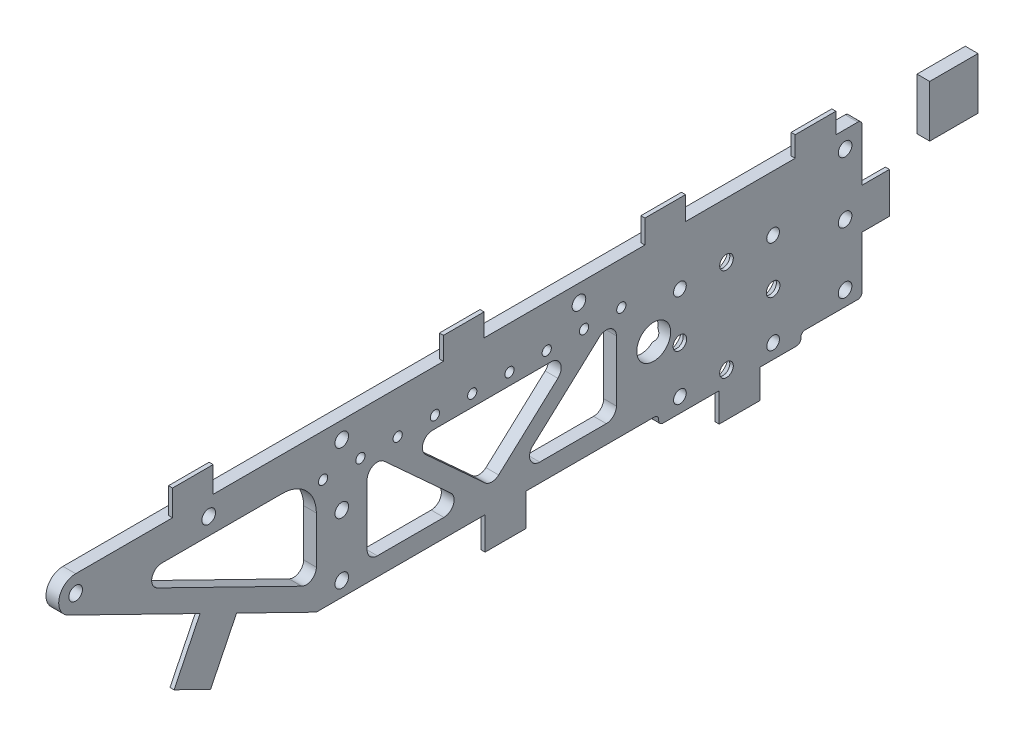
SolidWorks part; units mm, degrees
material "6061-T6 (SS)"
ref_plane "Front Plane" through (0, 0, 0) normal (0, 0, 1) x (1, 0, 0)
ref_plane "Top Plane" through (0, 0, 0) normal (0, 1, 0) x (1, 0, 0)
ref_plane "Right Plane" through (0, 0, 0) normal (1, 0, 0) x (0, 0, -1)
sketch "Sketch1" plane through (0, 0, 0) normal (1, 0, 0) x (0, 0, -1)
  line L0 (0, 0) -> (407.9875, 0) construction
  line L1 (407.9875, 76.2) -> (363.8474, 76.2) construction
  line L2 (407.9875, 76.2) -> (337.2485, 76.2) construction
  line L3 (0, 2.286) -> (405.7015, 2.286) construction
  line L7 (399.161, 66.167) -> (399.161, 8.5725)
  line L8 (373.761, 2.4765) -> (322.961, 2.4765) construction
  line L9 (373.761, 2.4765) -> (373.761, 53.2765) construction
  line L10 (373.761, 53.2765) -> (322.961, 53.2765) construction
  line L11 (322.961, 2.4765) -> (322.961, 53.2765) construction
  line L12 (407.9875, 0) -> (407.9875, 76.2) construction
  line L13 (405.7015, 2.286) -> (405.7015, 73.914) construction
  line L14 (405.7015, 73.914) -> (337.2485, 73.914) construction
  line L15 (405.7015, 73.914) -> (363.8474, 73.914) construction
  line L16 (373.9515, 2.286) -> (373.9515, 33.9264) construction
  line L17 (370.586, 50.1015) -> (326.136, 50.1015) construction
  line L18 (326.136, 5.6515) -> (326.136, 50.1015) construction
  line L19 (370.586, 5.6515) -> (326.136, 5.6515) construction
  line L20 (370.586, 5.6515) -> (370.586, 50.1015) construction
  line L21 (330.8985, 10.414) -> (330.8985, 45.339) construction
  line L22 (365.8235, 45.339) -> (330.8985, 45.339) construction
  line L23 (365.8235, 10.414) -> (365.8235, 45.339) construction
  line L24 (365.8235, 10.414) -> (330.8985, 10.414) construction
  line L25 (-107.0632, 2.286) -> (405.7015, 2.286) construction
  line L26 (-107.0632, 0) -> (407.9875, 0) construction
  line L27 (376.2375, 2.286) -> (376.2375, 33.9264) construction
  line L28 (373.9515, 33.9264) -> (376.2375, 33.9264) construction
  line L29 (337.2485, 76.2) -> (337.2485, 73.914) construction
  line L30 (0, 28.3777) -> (329.9656, 33.1402) construction
  line L31 (329.9656, 33.1402) -> (321.0756, 33.1402) construction
  line L32 (194.6275, 71.628) -> (194.6275, 2.286) construction
  line L33 (213.6775, 2.286) -> (213.6775, 71.628) construction
  line L34 (194.6275, 2.286) -> (213.6775, 2.286) construction
  line L35 (194.6275, 71.628) -> (213.6775, 71.628) construction
  line L36 (399.161, 71.628) -> (0, 71.628) construction
  line L37 (94.8817, 71.628) -> (113.9317, 71.628) construction
  line L38 (94.8817, 71.628) -> (94.8817, 2.286) construction
  line L39 (94.8817, 2.286) -> (113.9317, 2.286) construction
  line L40 (113.9317, 71.628) -> (113.9317, 2.286) construction
  line L41 (343.7851, 73.914) -> (343.7851, 71.628) construction
  line L42 (405.7015, 4.7625) -> (0, 4.7625) construction
  line L43 (204.1525, 59.817) -> (204.1525, 14.097) construction
  line L44 (204.1525, 36.957) -> (213.6775, 36.957) construction
  line L45 (104.4067, 59.817) -> (104.4067, 14.097) construction
  line L46 (399.161, 66.167) -> (104.4067, 66.167)
  line L47 (322.961, 8.5725) -> (322.961, 4.953)
  line L48 (322.961, 4.953) -> (376.2375, 4.953)
  line L50 (376.2375, 4.953) -> (376.2375, 8.5725)
  line L51 (376.2375, 8.5725) -> (399.161, 8.5725)
  line L52 (204.1525, 59.817) -> (104.4067, 59.817) construction
  line L53 (104.4067, 53.467) -> (194.6275, 53.467)
  line L54 (194.6275, 8.5725) -> (194.6275, 53.467)
  line L55 (194.6275, 8.5725) -> (322.961, 8.5725)
  line L56 (392.811, 59.817) -> (392.811, 14.097) construction
  line L57 (204.1525, 59.817) -> (392.811, 59.817) construction
  line L58 (392.811, 71.628) -> (392.811, 59.817) construction
  line L64 (405.7015, 73.914) -> (0, 73.914) construction
  circle A0 centre (330.8985, 45.339) radius 2.3813
  circle A1 centre (365.8235, 45.339) radius 2.3813
  circle A2 centre (330.8985, 10.414) radius 2.3813
  circle A3 centre (365.8235, 10.414) radius 2.3813
  circle A4 centre (321.0756, 33.1402) radius 6.35
  circle A5 centre (0, 28.3777) radius 22.2817 construction
  arc A6 (104.4067, 53.467) -> (104.4067, 66.167) centre (104.4067, 59.817) cw
  point P54 (204.1525, 2.286)
  point P66 (104.4067, 36.957)
  point P67 (104.4067, 2.286)
  dimension "D19" = 12.7
  dimension "D20" = 44.5634
  dimension "D3" = 50.8
  dimension "D2" = 0.1905
  dimension "D9" = 34.925
  dimension "D13" = 407.9875
  dimension "D14" = 0.1905
  dimension "D4" = 31.75
  dimension "D15" = 330
  dimension "D17" = 4.7625
  dimension "D18" = 8.89
  dimension "D21" = 3.81
  dimension "D16" = 19.05
  dimension "D25" = 45.72
  dimension "D22" = 213.36
  dimension "D7" = 104.4067
  dimension "D24" = 0.1905
  dimension "D11" = 6.35
  dimension "D23" = 12.8905
  dimension "D12" = 6.35
  dimension "D8" = 3.175
extrude "Boss-Extrude1" add sketch "Sketch1" along normal blind 4.7625
hole_wizard "CSK for #10 Flat Head Socket Cap Screw1" positions "Sketch2" profile "Sketch3" countersink size "#10" standard "ANSI Inch" end condition through all
sketch "Sketch2" plane through (0, 0, 0) normal (-1, 0, 0) x (0, 0, 1)
  line L0 (-365.8235, 45.339) -> (-330.8985, 10.414) construction
  line L9 (-365.8235, 27.8765) -> (-330.8985, 27.8765) construction
  line L11 (-348.361, 45.339) -> (-348.361, 10.414) construction
  point P58 (-348.361, 27.8765)
  point P59 (-348.361, 27.8765)
  point P62 (-348.361, 45.339)
  point P65 (-330.8985, 27.8765)
  point P68 (-365.8235, 27.8765)
  point P71 (-348.361, 10.414)
sketch "Sketch3" plane through (0, 10.414, -348.361) normal (0, 1, 0) x (0, 0, 1)
  line L0 (0, 0) -> (0, 4.7625)
  line L1 (0, 4.7625) -> (2.5527, 4.7625)
  line L2 (2.5527, 4.7625) -> (2.5527, 3.449)
  line L3 (2.5527, 3.449) -> (5.5509, 0)
  line L5 (5.5509, 0) -> (0, 0)
  line L6 (-2.5527, 3.449) -> (-5.5509, 0) construction
  line L11 (0, -6.35) -> (0, 107.95) construction
  dimension "Thru Hole Dia." = 5.1054
  dimension "Thru Hole Depth" = 4.7625
  dimension "Near C'Sink Dia." = 11.1018
  dimension "Near C'Sink Angle" = 82
sketch "Sketch13" plane through (0, 0, 0) normal (-1, 0, 0) x (0, 0, 1)
  line L0 (-194.6275, 8.5725) -> (-101.6143, 54.1139)
  line L1 (-194.6275, 17.0569) -> (-120.2639, 53.467)
  line L2 (-194.6275, 53.467) -> (-194.6275, 8.5725) construction
  line L3 (-104.4067, 53.467) -> (-194.6275, 53.467) construction
  line L4 (-194.6275, 17.0569) -> (-194.6275, 8.5725)
  line L5 (-120.2639, 53.467) -> (-101.6143, 54.1139)
  arc A0 (-104.4067, 53.467) -> (-104.4067, 66.167) centre (-104.4067, 59.817) ccw construction
  dimension "D1" = 7.62
extrude "Boss-Extrude3" add sketch "Sketch13" against normal up to vertex (4.7625 mm away) up to point (4.7625, 8.5725, -194.6275)
fillet "Fillet1" radius 1.5875 7 edges at (2.3813, 66.167, -399.161) (2.3813, 4.953, -376.2375) (2.3813, 4.953, -322.961) (2.3813, 8.5725, -376.2375) (2.3813, 8.5725, -399.161) (2.3813, 8.5725, -322.961) (2.3813, 8.5725, -194.6275)
fillet "Fillet2" radius 12.7 1 edges at (2.3813, 53.467, -194.6275)
hole_wizard "#10 Clearance Hole1" positions "Sketch8" profile "Sketch9" hole size "#10" standard "ANSI Inch" end condition through all
sketch "Sketch8" plane through (4.7625, 0, 0) normal (1, 0, 0) x (0, 0, -1)
  line L1 (204.1525, 59.817) -> (204.1525, 14.097) construction
  line L6 (204.1525, 59.817) -> (104.4067, 59.817) construction
  line L7 (392.811, 59.817) -> (392.811, 14.097) construction
  line L8 (204.1525, 59.817) -> (293.0525, 59.817) construction
  line L9 (204.1525, 59.817) -> (392.811, 59.817) construction
  line L10 (293.0525, 59.817) -> (392.811, 59.817) construction
  point P10 (204.1525, 59.817)
  point P13 (204.1525, 36.957)
  point P17 (204.1525, 14.097)
  point P30 (154.2796, 59.817)
  point P34 (392.811, 59.817)
  point P37 (392.811, 36.957)
  point P41 (392.811, 14.097)
  point P56 (293.0525, 59.817)
  point P68 (104.4067, 59.817)
  dimension "D1" = 88.9
sketch "Sketch9" plane through (4.7625, 59.817, -204.1525) normal (0, 1, 0) x (0, 0, -1)
  line L0 (0, 0) -> (0, 5.0174)
  line L1 (0, 5.0174) -> (2.5527, 5.0174)
  line L2 (2.5527, 5.0174) -> (2.5527, 0)
  line L5 (2.5527, 0) -> (0, 0)
  line L11 (0, -6.35) -> (0, 107.95) construction
  dimension "Thru Hole Dia." = 5.1054
  dimension "Thru Hole Depth" = 5.0174
sketch "Sketch14" plane through (0, 0, 0) normal (-1, 0, 0) x (0, 0, 1)
  line L0 (-194.6275, 36.957) -> (-213.6775, 36.957) construction
  line L1 (-307.1056, 15.4305) -> (-213.6775, 15.4305)
  line L2 (-307.1056, 15.4305) -> (-307.1056, 45.847)
  line L3 (-307.1056, 45.847) -> (-213.6775, 45.847)
  line L4 (-213.6775, 15.4305) -> (-213.6775, 45.847)
  line L5 (-194.6275, 40.767) -> (-194.6275, 17.0569) construction
  line L6 (-194.9953, 8.5725) -> (-321.3735, 8.5725) construction
  line L7 (-252.2487, 15.4305) -> (-218.9662, 45.847)
  line L8 (-261.6616, 15.4305) -> (-228.3791, 45.847)
  line L9 (-397.5735, 66.167) -> (-104.4067, 66.167) construction
  line L10 (-259.1216, 15.4305) -> (-292.4041, 45.847)
  line L11 (-268.5344, 15.4305) -> (-300.7254, 44.8494)
  line L12 (-245.0203, 30.6387) -> (-240.7365, 25.9513) construction
  line L13 (-275.7628, 30.6387) -> (-280.0466, 25.9513) construction
  circle A0 centre (-204.1525, 36.957) radius 2.5527 construction
  arc A1 (-213.6775, 42.037) -> (-220.0578, 44.8494) centre (-217.4875, 42.037) ccw
  arc A2 (-300.7254, 44.8494) -> (-307.1056, 42.037) centre (-303.2956, 42.037) ccw
  arc A3 (-325.3796, 28.4713) -> (-327.3467, 32.1424) centre (-321.0756, 33.1402) ccw construction
  point P8 (-204.1525, 36.957)
  dimension "D2" = 3.81
  dimension "D6" = 2.54
  dimension "D1" = 6.858
  dimension "D3" = 6.35
  dimension "D4" = 20.32
  dimension "D5" = 7.62
extrude "Cut-Extrude1" cut sketch "Sketch14" against normal through all contours L10 L8 L3 | L4 A1 L7 L1 | L11 A2 L2 L1
fillet "Fillet3" radius 3.81 9 edges at (2.3813, 17.0569, -194.6275) (2.3813, 53.467, -120.2639) (2.3813, 15.4305, -252.2487) (2.3813, 15.4305, -213.6775) (2.3813, 15.4305, -307.1056) (2.3813, 15.4305, -268.5344) (2.3813, 45.847, -228.3791) (2.3813, 16.5911, -260.3916) (2.3813, 45.847, -292.4041)
sketch "Sketch10" [suppressed] plane through (4.7625, 0, 0) normal (1, 0, 0) x (0, 0, -1)
  line L0 (196.215, 8.5725) -> (170.815, 8.5725)
  line L1 (169.2275, 10.16) -> (169.2275, 40.767)
  line L2 (136.7096, 53.467) -> (181.9275, 53.467) construction
  line L3 (156.5275, 53.467) -> (196.215, 53.467)
  line L4 (196.215, 53.467) -> (196.215, 8.5725)
  line L5 (194.6275, 40.767) -> (194.6275, 23.1645) construction
  arc A0 (170.815, 8.5725) -> (169.2275, 10.16) centre (170.815, 10.16) cw
  arc A1 (169.2275, 40.767) -> (156.5275, 53.467) centre (156.5275, 40.767) ccw
  arc A2 (194.6275, 40.767) -> (181.9275, 53.467) centre (181.9275, 40.767) ccw construction
  arc A3 (194.6275, 10.16) -> (196.215, 8.5725) centre (196.215, 10.16) ccw construction
  dimension "D1" = 25.4
extrude "Boss-Extrude2" [suppressed] add sketch "Sketch10" against normal up to vertex
hole_wizard "#8-32 Tapped Hole1" positions "Sketch11" profile "Sketch12" tap size "#8-32" standard "ANSI Inch"
sketch "Sketch11" plane through (4.7625, 0, 0) normal (1, 0, 0) x (0, 0, -1)
  line L5 (280.9875, 50.292) -> (308.9275, 50.292) construction
  circle A0 centre (204.1525, 59.817) radius 2.5527 construction
  point P0 (197.1675, 50.292)
  point P12 (211.1375, 50.292)
  point P13 (225.1075, 50.292)
  point P14 (239.0775, 50.292)
  point P15 (253.0475, 50.292)
  point P16 (267.0175, 50.292)
  point P17 (280.9875, 50.292)
  point P18 (294.9575, 50.292)
  point P41 (308.9275, 50.292)
  point P43 (204.1525, 35.052) [skipped]
  point P44 (301.9425, 35.052) [skipped]
  point P45 (287.9725, 35.052) [skipped]
  point P46 (274.0025, 35.052) [skipped]
  point P47 (260.0325, 35.052) [skipped]
  point P48 (246.0625, 35.052) [skipped]
  point P49 (232.0925, 35.052) [skipped]
  point P50 (218.1225, 35.052) [skipped]
  dimension "D1" = 9.525
  dimension "D2" = 6.985
  dimension "D5" = 13.97
  dimension "D3" = 8
  dimension "D4" = 2
sketch "Sketch12" plane through (4.7625, 50.292, -197.1675) normal (0, 1, 0) x (0, 0, -1)
  line L0 (0, 0) -> (0, 5.0174)
  line L1 (0, 5.0174) -> (1.7272, 5.0174)
  line L2 (1.7272, 5.0174) -> (1.7272, 0)
  line L5 (1.7272, 0) -> (0, 0)
  line L11 (0, -6.35) -> (0, 107.95) construction
  dimension "Thru Tap Drill Dia." = 3.4544
  dimension "Thru Tap Drill Depth" = 5.0174
cosmetic thread "Hole Thread1" parameters "D2"=4.1656
cosmetic thread "Hole Thread13" parameters "D2"=4.1656
cosmetic thread "Hole Thread14" parameters "D2"=4.1656
cosmetic thread "Hole Thread15" parameters "D2"=4.1656
cosmetic thread "Hole Thread16" parameters "D2"=4.1656
cosmetic thread "Hole Thread17" parameters "D2"=4.1656
cosmetic thread "Hole Thread18" parameters "D2"=4.1656
cosmetic thread "Hole Thread19" parameters "D2"=4.1656
cosmetic thread "Hole Thread20" parameters "D2"=4.1656
sketch "Sketch15" plane through (4.7625, 0, 0) normal (1, 0, 0) x (0, 0, -1)
  line L1 (424.5243, 65.9065) -> (442.6264, 65.9065)
  line L2 (424.5243, 65.9065) -> (424.5243, 46.5137)
  line L3 (424.5243, 46.5137) -> (442.6264, 46.5137)
  line L4 (442.6264, 65.9065) -> (442.6264, 46.5137)
  line L5 (424.5243, 65.9065) -> (442.6264, 46.5137) construction
  line L6 (424.5243, 46.5137) -> (442.6264, 65.9065) construction
  point P4 (433.5754, 56.2101)
extrude "Boss-Extrude4" add sketch "Sketch15" against normal up to surface (4.7625 mm away) separate body up to face at (0, 50.292, -195.4403)
sketch "Sketch16" plane through (4.7625, 0, 0) normal (-1, 0, 0) x (0, 0, 1)
  line L0 (-389.3419, 66.167) -> (-374.1019, 66.167)
  line L1 (-389.3419, 66.167) -> (-389.3419, 73.8187)
  line L2 (-374.1019, 66.167) -> (-374.1019, 73.8187)
  line L3 (-389.3419, 73.8187) -> (-374.1019, 73.8187)
  line L4 (-397.5735, 66.167) -> (-104.4067, 66.167) construction
  line L5 (-333.0124, 66.167) -> (-317.7724, 66.167)
  line L6 (-333.0124, 66.167) -> (-333.0124, 74.9228)
  line L7 (-317.7724, 66.167) -> (-317.7724, 74.9228)
  line L8 (-333.0124, 74.9228) -> (-317.7724, 74.9228)
  line L9 (-257.504, 66.167) -> (-242.264, 66.167)
  line L10 (-257.504, 66.167) -> (-257.504, 74.6077)
  line L11 (-242.264, 66.167) -> (-242.264, 74.6077)
  line L12 (-257.504, 74.6077) -> (-242.264, 74.6077)
  line L13 (-155.9499, 66.167) -> (-140.7099, 66.167)
  line L14 (-155.9499, 66.167) -> (-155.9499, 75.8213)
  line L15 (-140.7099, 66.167) -> (-140.7099, 75.8213)
  line L16 (-155.9499, 75.8213) -> (-140.7099, 75.8213)
  line L17 (-151.0336, 29.9171) -> (-164.721, 23.2154)
  line L18 (-151.0336, 29.9171) -> (-141.2965, 10.0301)
  line L19 (-164.721, 23.2154) -> (-154.9839, 3.3284)
  line L20 (-141.2965, 10.0301) -> (-154.9839, 3.3284)
  line L21 (-194.2972, 8.7342) -> (-101.6143, 54.1139) construction
  line L22 (-257.8762, 8.5725) -> (-273.1162, 8.5725)
  line L23 (-257.8762, 8.5725) -> (-257.8762, -3.5748)
  line L24 (-273.1162, 8.5725) -> (-273.1162, -3.5748)
  line L25 (-257.8762, -3.5748) -> (-273.1162, -3.5748)
  line L26 (-194.9953, 8.5725) -> (-321.3735, 8.5725) construction
  line L27 (-345.6202, 4.953) -> (-360.8602, 4.953)
  line L28 (-345.6202, 4.953) -> (-345.6202, -5.8855)
  line L29 (-360.8602, 4.953) -> (-360.8602, -5.8855)
  line L30 (-345.6202, -5.8855) -> (-360.8602, -5.8855)
  line L31 (-324.5485, 4.953) -> (-347.366, 4.953) construction
  line L32 (-349.356, 4.953) -> (-374.65, 4.953) construction
  line L33 (-399.161, 29.6565) -> (-399.161, 44.8965)
  line L34 (-399.161, 29.6565) -> (-409.4238, 29.6565)
  line L35 (-399.161, 44.8965) -> (-409.4238, 44.8965)
  line L36 (-409.4238, 29.6565) -> (-409.4238, 44.8965)
  line L37 (-399.161, 10.16) -> (-399.161, 64.5795) construction
  dimension "D1" = 15.24
extrude "Boss-Extrude5" add sketch "Sketch16" along normal blind 1.524
equation "\"D20@Sketch1\"=28*5mm / pi"
